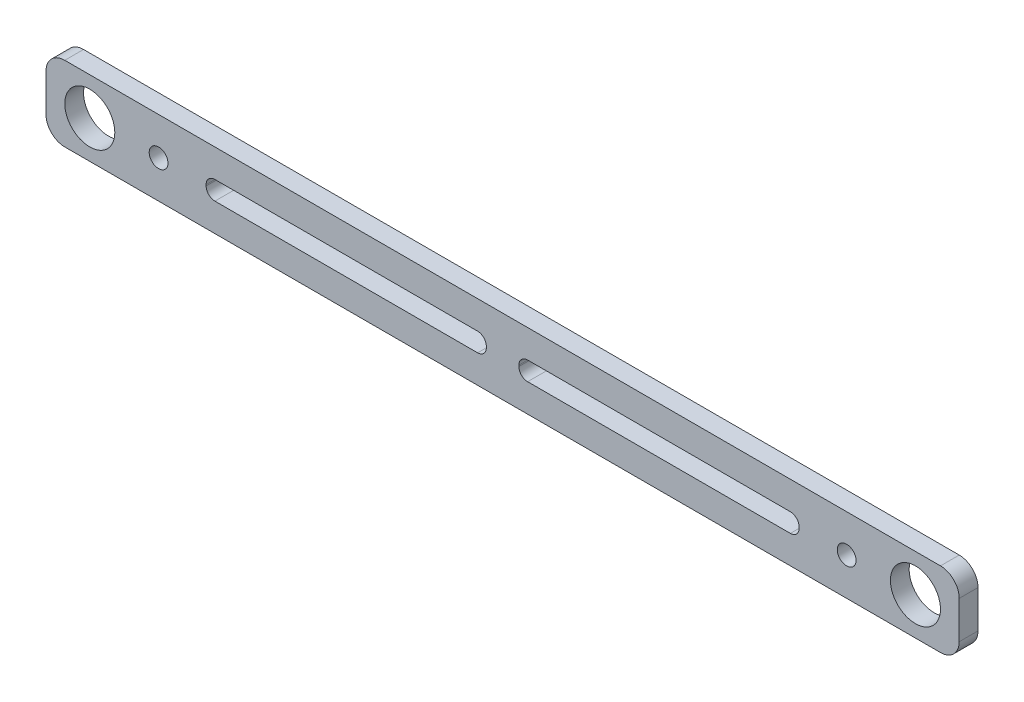
SolidWorks part; units mm, degrees
material "Maple"
ref_plane "Front Plane" through (0, 0, 0) normal (0, 0, 1) x (1, 0, 0)
ref_plane "Top Plane" through (0, 0, 0) normal (0, 1, 0) x (1, 0, 0)
ref_plane "Right Plane" through (0, 0, 0) normal (1, 0, 0) x (0, 0, -1)
sketch "Sketch1" plane through (0, 0, 0) normal (0, 0, 1) x (1, 0, 0)
  line L0 (0, 0) -> (-25, 0) construction
  line L1 (-70, 6) -> (70, 6)
  line L2 (-73, 3) -> (-73, -3)
  line L3 (-70, -6) -> (70, -6)
  line L4 (73, 3) -> (73, -3)
  line L5 (-73, 6) -> (73, -6) construction
  line L6 (-73, -6) -> (73, 6) construction
  line L7 (-46, 1.5) -> (-4, 1.5)
  line L8 (-47.4, 0.1) -> (-47.4, -0.1)
  line L9 (-46, -1.5) -> (-4, -1.5)
  line L10 (-2.6, 0.1) -> (-2.6, -0.1)
  line L11 (-47.4, 1.5) -> (-2.6, -1.5) construction
  line L12 (-47.6, -1.4933) -> (-2.6, 1.5) construction
  line L13 (4, 1.5) -> (46, 1.5)
  line L14 (2.6, 0.1) -> (2.6, -0.1)
  line L15 (4, -1.5) -> (46, -1.5)
  line L16 (47.4, 0.1) -> (47.4, -0.1)
  line L17 (2.6, 1.5) -> (47.4, -1.5) construction
  line L19 (0, 0) -> (25, 0) construction
  arc A0 (70, -6) -> (73, -3) centre (70, -3) ccw
  arc A1 (73, 3) -> (70, 6) centre (70, 3) ccw
  arc A2 (-70, -6) -> (-73, -3) centre (-70, -3) cw
  arc A3 (-70, 6) -> (-73, 3) centre (-70, 3) ccw
  circle A5 centre (-66, 0) radius 4
  circle A6 centre (66, 0) radius 4
  arc A7 (-2.6, -0.1) -> (-4, -1.5) centre (-4, -0.1) cw
  arc A8 (-2.6, 0.1) -> (-4, 1.5) centre (-4, 0.1) ccw
  arc A9 (-46, 1.5) -> (-47.4, 0.1) centre (-46, 0.1) ccw
  arc A10 (-46, -1.5) -> (-47.4, -0.1) centre (-46, -0.1) cw
  arc A11 (47.4, -0.1) -> (46, -1.5) centre (46, -0.1) cw
  arc A12 (47.4, 0.1) -> (46, 1.5) centre (46, 0.1) ccw
  arc A13 (4, 1.5) -> (2.6, 0.1) centre (4, 0.1) ccw
  arc A14 (4, -1.5) -> (2.6, -0.1) centre (4, -0.1) cw
  circle A15 centre (-55, 0) radius 1.5
  circle A16 centre (55, 0) radius 1.5
  point P0 (0, 0)
  point P5 (0, 0)
  point P18 (0, 0)
  point P26 (-25, 0)
  point P46 (0, 0)
  point P47 (25, 0)
  dimension "D3" = 3
  dimension "D6" = 8
  dimension "D7" = 1.4
  dimension "D10" = 21
  dimension "D15" = 3
  dimension "D1" = 146
  dimension "D2" = 12
  dimension "D4" = 45
  dimension "D5" = 3
  dimension "D8" = 25
  dimension "D9" = 3
  dimension "D11" = 25
  dimension "D12" = 3
  dimension "D13" = 7
  dimension "D14" = 55
  dimension "D16" = 110
  dimension "D17" = 7
extrude "Boss-Extrude1" add sketch "Sketch1" along normal blind 3
